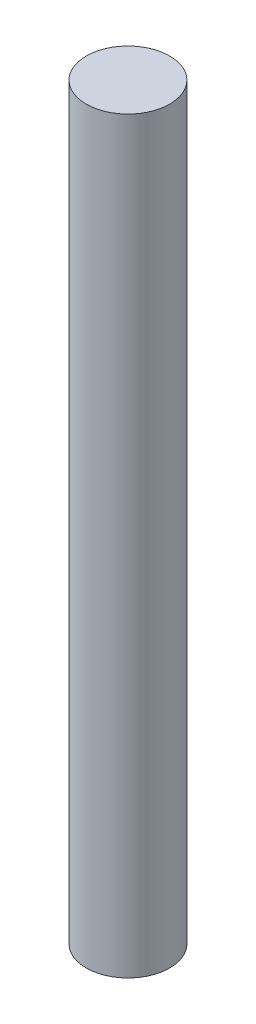
SolidWorks part; units mm, degrees
ref_plane "Front Plane" through (0, 0, 0) normal (0, 0, 1) x (1, 0, 0)
ref_plane "Top Plane" through (0, 0, 0) normal (0, 1, 0) x (1, 0, 0)
ref_plane "Right Plane" through (0, 0, 0) normal (1, 0, 0) x (0, 0, -1)
sketch "Sketch2" plane through (0, 0, 0) normal (0, 1, 0) x (1, 0, 0)
  line L0 (0, 0) -> (0, 236.0808) construction
  circle A0 centre (0, 0) radius 26.2
  dimension "D1" = 52.4
extrude "Boss-Extrude1" add sketch "Sketch2" along normal blind 100 and the other way blind 370
